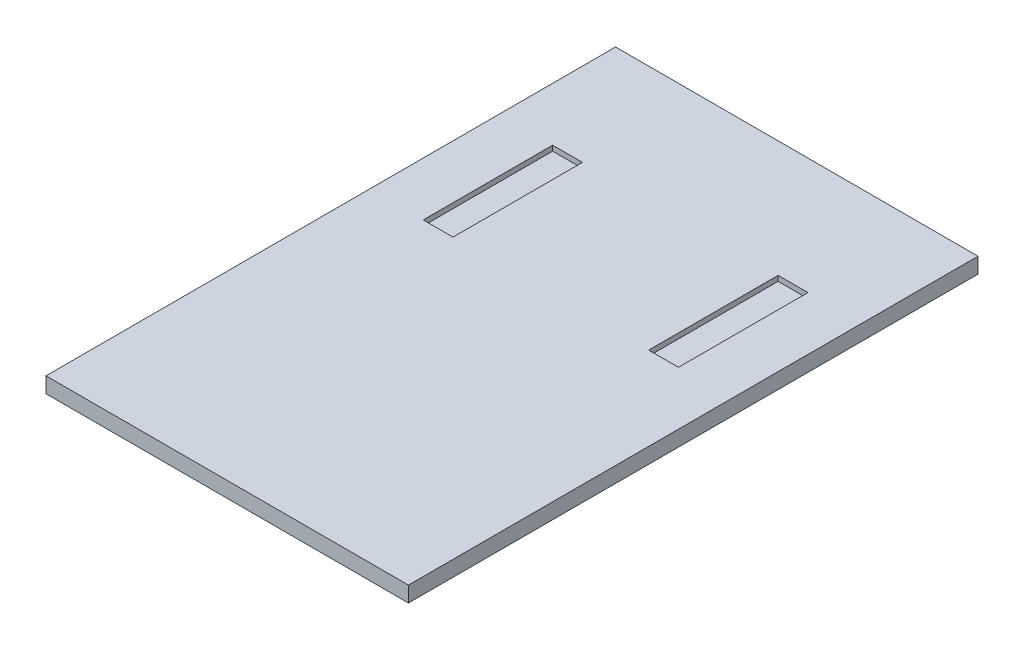
SolidWorks part; units mm, degrees
ref_plane "Front Plane" through (0, 0, 0) normal (0, 0, 1) x (1, 0, 0)
ref_plane "Top Plane" through (0, 0, 0) normal (0, 1, 0) x (1, 0, 0)
ref_plane "Right Plane" through (0, 0, 0) normal (1, 0, 0) x (0, 0, -1)
sketch "Sketch1" plane through (0, 0, 0) normal (0, 1, 0) x (1, 0, 0)
  line L1 (-889, -1397) -> (889, -1397)
  line L2 (-889, -1397) -> (-889, 1397)
  line L3 (-889, 1397) -> (889, 1397)
  line L4 (889, -1397) -> (889, 1397)
  line L5 (-889, -1397) -> (889, 1397) construction
  line L6 (-889, 1397) -> (889, -1397) construction
  point P0 (0, 0)
  dimension "D1" = 2794
  dimension "D2" = 1778
extrude "Boss-Extrude1" add sketch "Sketch1" along normal blind 76.2
sketch "Sketch3" plane through (0, 76.2, 0) normal (0, 1, 0) x (1, 0, 0)
  line L0 (889, 1397) -> (-889, 1397) construction
  line L1 (626.11, 190.5) -> (480.06, 190.5)
  line L2 (626.11, 190.5) -> (626.11, 825.5)
  line L3 (626.11, 825.5) -> (480.06, 825.5)
  line L4 (480.06, 190.5) -> (480.06, 825.5)
  line L5 (626.11, 190.5) -> (480.06, 825.5) construction
  line L6 (626.11, 825.5) -> (480.06, 190.5) construction
  line L7 (889, -1397) -> (889, 1397) construction
  line L8 (0, -1397) -> (0, 1397) construction
  line L9 (-889, -1397) -> (889, -1397) construction
  line L10 (-626.11, 825.5) -> (-480.06, 190.5) construction
  line L11 (-626.11, 190.5) -> (-480.06, 825.5) construction
  line L12 (-480.06, 190.5) -> (-480.06, 825.5)
  line L13 (-626.11, 825.5) -> (-480.06, 825.5)
  line L14 (-626.11, 190.5) -> (-626.11, 825.5)
  line L15 (-626.11, 190.5) -> (-480.06, 190.5)
  point P0 (553.085, 508)
  point P17 (-553.085, 508)
  dimension "D1" = 571.5
  dimension "D2" = 635
  dimension "D3" = 146.05
  dimension "D4" = 262.89
extrude "Cut-Extrude1" cut sketch "Sketch3" against normal blind 25.4
